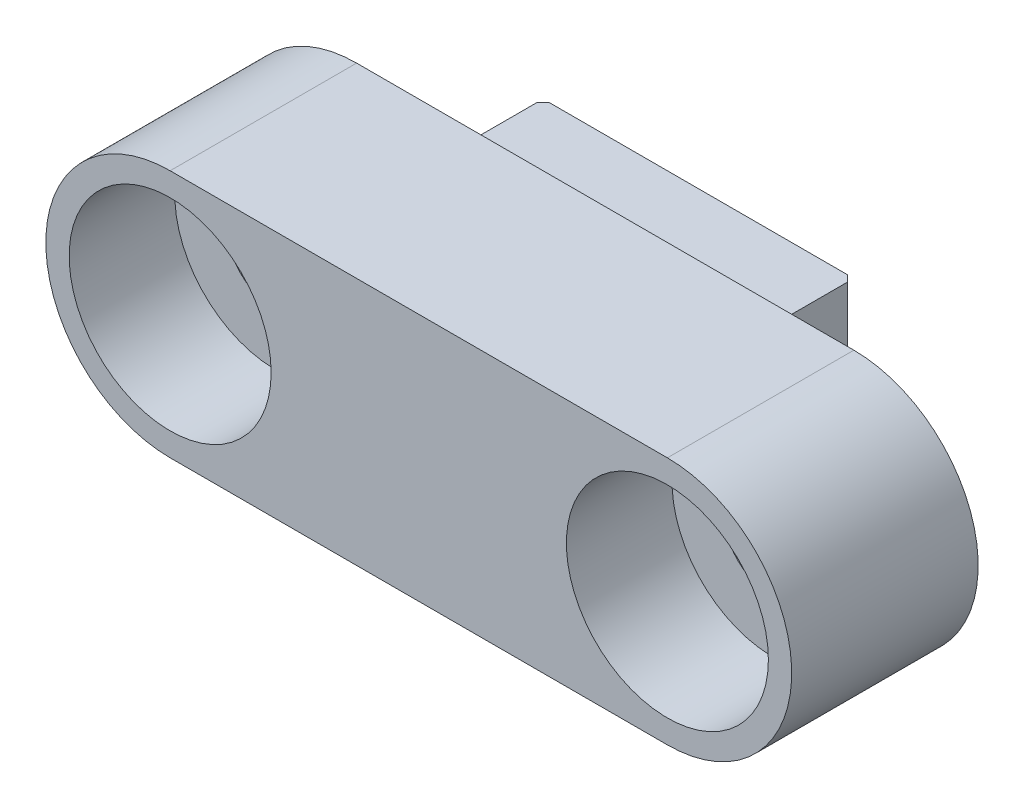
SolidWorks part; units mm, degrees
material "7075-O (SS)"
ref_plane "Face" through (0, 0, 0) normal (0, 0, 1) x (1, 0, 0)
ref_plane "Dessus" through (0, 0, 0) normal (0, 1, 0) x (1, 0, 0)
ref_plane "Droite" through (0, 0, 0) normal (1, 0, 0) x (0, 0, -1)
sketch "Esquisse1" plane through (0, 0, 0) normal (0, 0, 1) x (1, 0, 0)
  line L0 (-8, 4) -> (8, 4)
  line L1 (-8, -4) -> (8, -4)
  arc A0 (-8, 4) -> (-8, -4) centre (-8, 0) ccw
  arc A1 (8, -4) -> (8, 4) centre (8, 0) ccw
  dimension "D1" = 8
  dimension "D2" = 8
  dimension "D3" = 4
extrude "Boss.-Extru.1" add sketch "Esquisse1" along normal blind 6
hole_wizard "Chambrage pour vis à tête hexagonale M31" positions "Esquisse3" profile "Esquisse2" counterbore size "M3" standard "Iso" end condition through all
sketch "Esquisse3" plane through (0, 0, 6) normal (0, 0, 1) x (1, 0, 0)
  point P0 (-8, 0)
  point P2 (8, 0)
  dimension "D1" = 8
  dimension "D2" = 8
sketch "Esquisse2" plane through (-8, 0, 6) normal (1, 0, 0) x (0, -1, 0)
  line L0 (0, 0) -> (0, 6)
  line L1 (0, 6) -> (1.6, 6)
  line L3 (1.6, 6) -> (1.6, 3.4)
  line L4 (1.6, 3.4) -> (3.25, 3.4)
  line L5 (3.25, 3.4) -> (3.25, 0)
  line L7 (3.25, 0) -> (0, 0)
  line L11 (0, -6.35) -> (0, 107.95) construction
  dimension "Diamètre du perçage jusqu'au prochain" = 3.2
  dimension "Profondeur du perçage jusqu'au prochain" = 6
  dimension "Diamètre du chambrage" = 6.5
  dimension "Profondeur du chambrage" = 3.4
sketch "Esquisse6" plane through (0, 0, 0) normal (0, 0, -1) x (-1, 0, 0)
  line L0 (-8, 4) -> (8, 4) construction
  line L1 (-5, 4) -> (5, 4)
  line L2 (-5, 4) -> (-5, -4)
  line L3 (-5, -4) -> (5, -4)
  line L4 (5, 4) -> (5, -4)
  line L5 (8, -4) -> (-8, -4) construction
  dimension "D1" = 5
  dimension "D2" = 10
extrude "Boss.-Extru.2" add sketch "Esquisse6" along normal blind 3
chamfer "Chanfrein1" distance 0.2 angle 45 2 edges at (5, 0, -3) (-5, 0, -3)
hole_wizard "Trou taraudé M51" [suppressed] positions "Esquisse5" profile "Esquisse4" tap size "M5" standard "Iso"
sketch "Esquisse5" plane through (0, 0, 6) normal (0, 0, 1) x (1, 0, 0)
  point P0 (0, 0)
sketch "Esquisse4" plane through (0, 0, 6) normal (1, 0, 0) x (0, -1, 0)
  line L0 (0, 0) -> (0, 9)
  line L1 (0, 9) -> (2.1, 9)
  line L2 (2.1, 9) -> (2.1, 0)
  line L5 (2.1, 0) -> (0, 0)
  line L11 (0, -6.35) -> (0, 107.95) construction
  dimension "Diamètre du trou pour taraudage jusqu'au prochain" = 4.2
  dimension "Profondeur du trou pour taraudage jusqu'au prochain" = 9
cosmetic thread "Filetage de perçage1" [suppressed] parameters "D2"=5
sketch "Esquisse10" plane through (5, 0, 0) normal (1, 0, 0) x (0, 0, -1)
  line L1 (3, 4) -> (3, -4) construction
  line L2 (0, 4) -> (3, 4)
  line L3 (0, 4) -> (0, 3)
  line L4 (0, 3) -> (3, 3)
  line L6 (3, 4) -> (3, 3)
  line L8 (0, -4) -> (3, -4)
  line L9 (0, -4) -> (0, -3)
  line L10 (0, -3) -> (3, -3)
  line L11 (3, -4) -> (3, -3)
  dimension "D1" = 3
  dimension "D2" = 3
extrude "Enlèv. mat.-Extru.5" cut sketch "Esquisse10" against normal up to next
